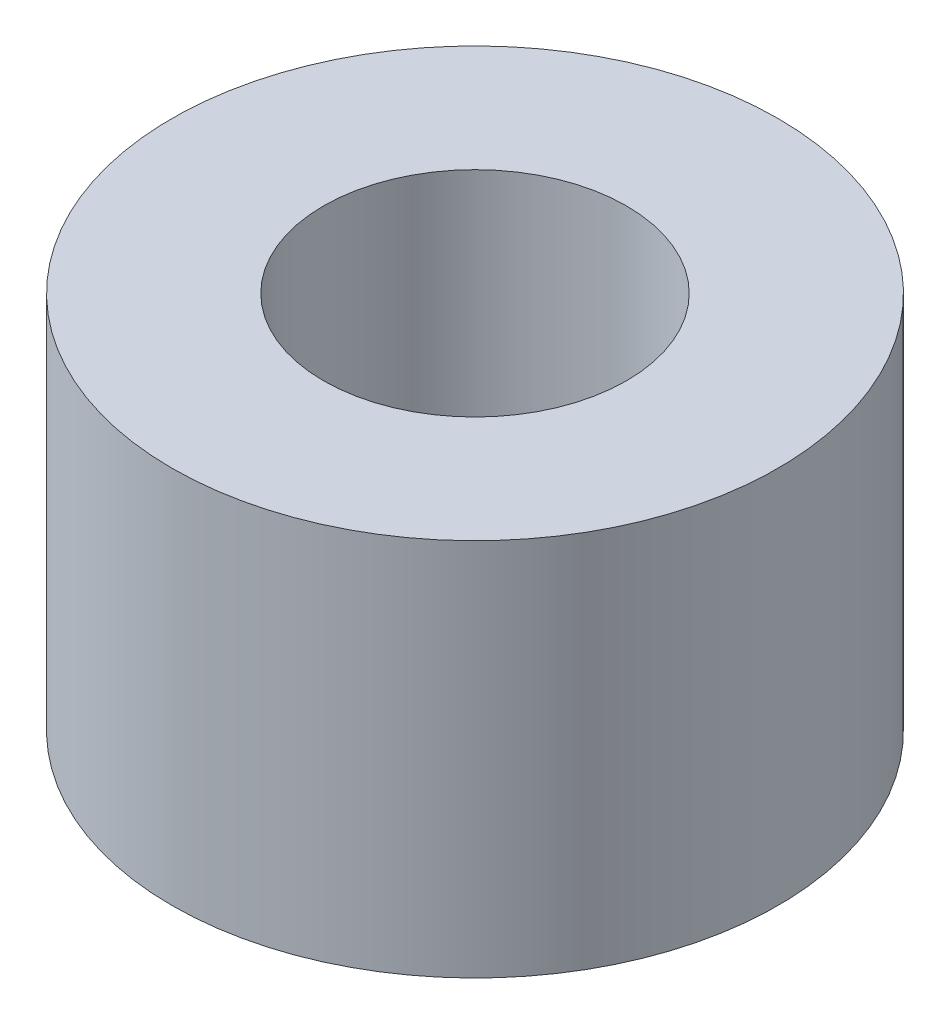
SolidWorks part; units mm, degrees
ref_plane "Plan de face" through (0, 0, 0) normal (0, 0, 1) x (1, 0, 0)
ref_plane "Plan de dessus" through (0, 0, 0) normal (0, 1, 0) x (1, 0, 0)
ref_plane "Plan de droite" through (0, 0, 0) normal (1, 0, 0) x (0, 0, -1)
sketch "Esquisse1" plane through (0, 0, 0) normal (0, 1, 0) x (1, 0, 0)
  circle A0 centre (0, 0) radius 4
  circle A1 centre (0, 0) radius 2
  dimension "D1" = 4
  dimension "D2" = 8
extrude "Boss.-Extru.1" add sketch "Esquisse1" along normal blind 5
